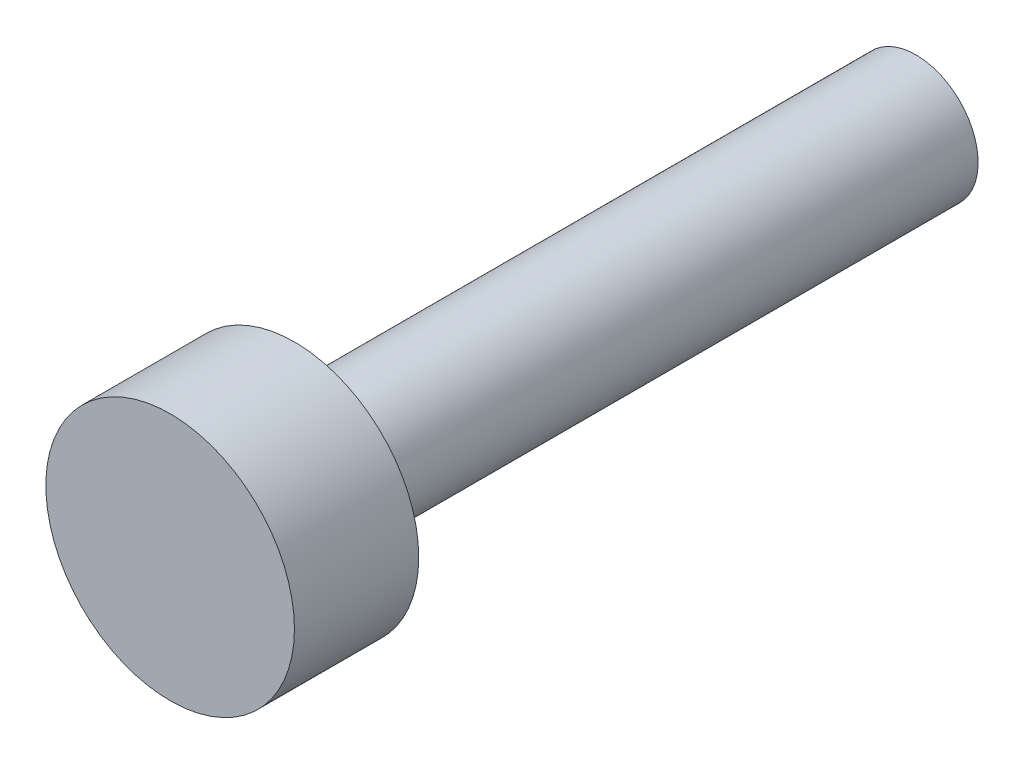
SolidWorks part; units mm, degrees
ref_plane "Front Plane" through (0, 0, 0) normal (0, 0, 1) x (1, 0, 0)
ref_plane "Top Plane" through (0, 0, 0) normal (0, 1, 0) x (1, 0, 0)
ref_plane "Right Plane" through (0, 0, 0) normal (1, 0, 0) x (0, 0, -1)
sketch "Sketch1" plane through (0, 0, 0) normal (0, 0, 1) x (1, 0, 0)
  circle A0 centre (0, 0) radius 1.5875
  dimension "D1" = 3.175
extrude "Boss-Extrude1" add sketch "Sketch1" along normal blind 19.05
sketch "Sketch2" plane through (0, 0, 19.05) normal (0, 0, 1) x (1, 0, 0)
  circle A0 centre (0, 0) radius 3.175
  dimension "D1" = 6.35
extrude "Boss-Extrude2" add sketch "Sketch2" against normal blind 3.175
